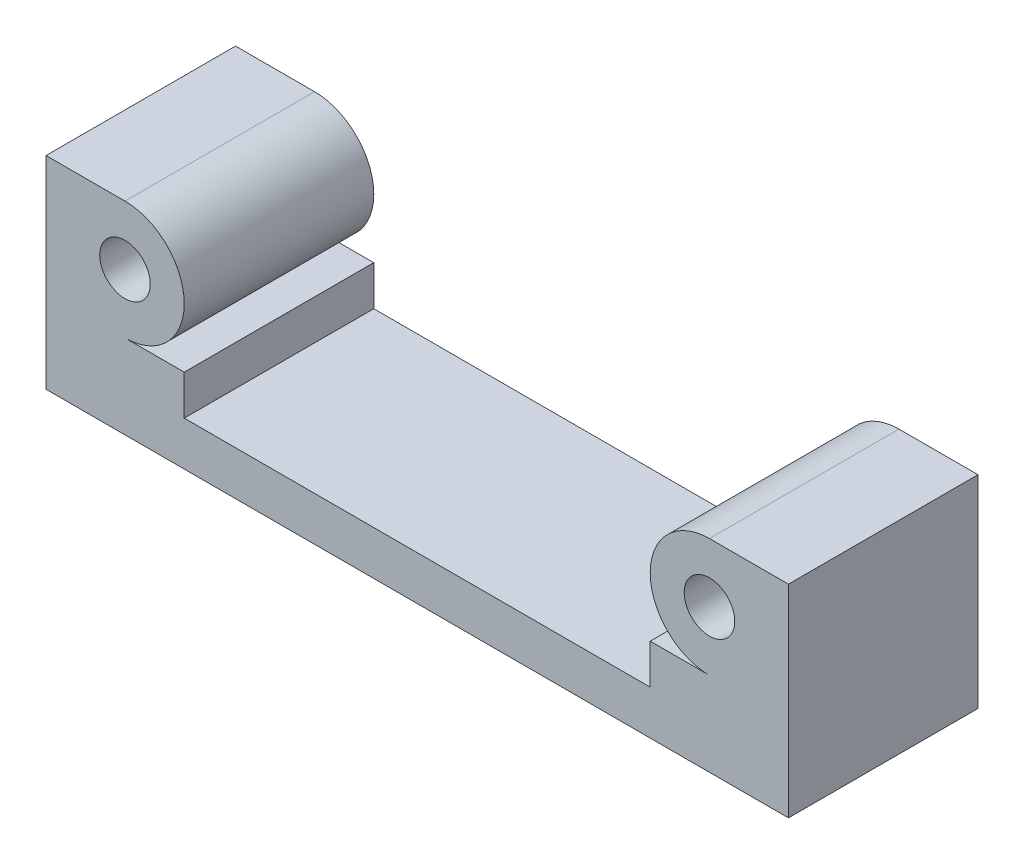
SolidWorks part; units mm, degrees
material "ABS"
ref_plane "Front Plane" through (0, 0, 0) normal (0, 0, 1) x (1, 0, 0)
ref_plane "Top Plane" through (0, 0, 0) normal (0, 1, 0) x (1, 0, 0)
ref_plane "Right Plane" through (0, 0, 0) normal (1, 0, 0) x (0, 0, -1)
sketch "Sketch1" plane through (0, 0, 0) normal (0, 0, 1) x (1, 0, 0)
  line L0 (-3.75, 10.0231) -> (-8.75, 10.0231)
  line L1 (-8.75, 10.0231) -> (-8.75, -2.7924)
  line L2 (-8.75, -2.7924) -> (38.25, -2.7924)
  line L3 (38.25, -2.7924) -> (38.25, 10.0231)
  line L4 (38.25, 10.0231) -> (33.25, 10.0231)
  line L6 (33.25, 2.5231) -> (38.25, 2.5231)
  line L7 (-3.75, 2.5231) -> (-8.75, 2.5231)
  line L10 (-3.75, 2.5231) -> (0, 2.5231)
  line L11 (0, 2.5231) -> (0, 0)
  line L12 (0, 0) -> (29.5, 0)
  line L13 (29.5, 0) -> (29.5, 2.5231)
  line L14 (29.5, 2.5231) -> (33.25, 2.5231)
  circle A0 centre (-3.75, 6.2731) radius 1.6
  circle A1 centre (-3.75, 6.2731) radius 3.75
  circle A2 centre (33.25, 6.2731) radius 1.6
  circle A3 centre (33.25, 6.2731) radius 3.75
  circle A4 centre (33.25, 6.2731) radius 3.75
  dimension "D1" = 5
  dimension "D2" = 5
extrude "Boss-Extrude1" add sketch "Sketch1" along normal up to surface (12 mm away)
